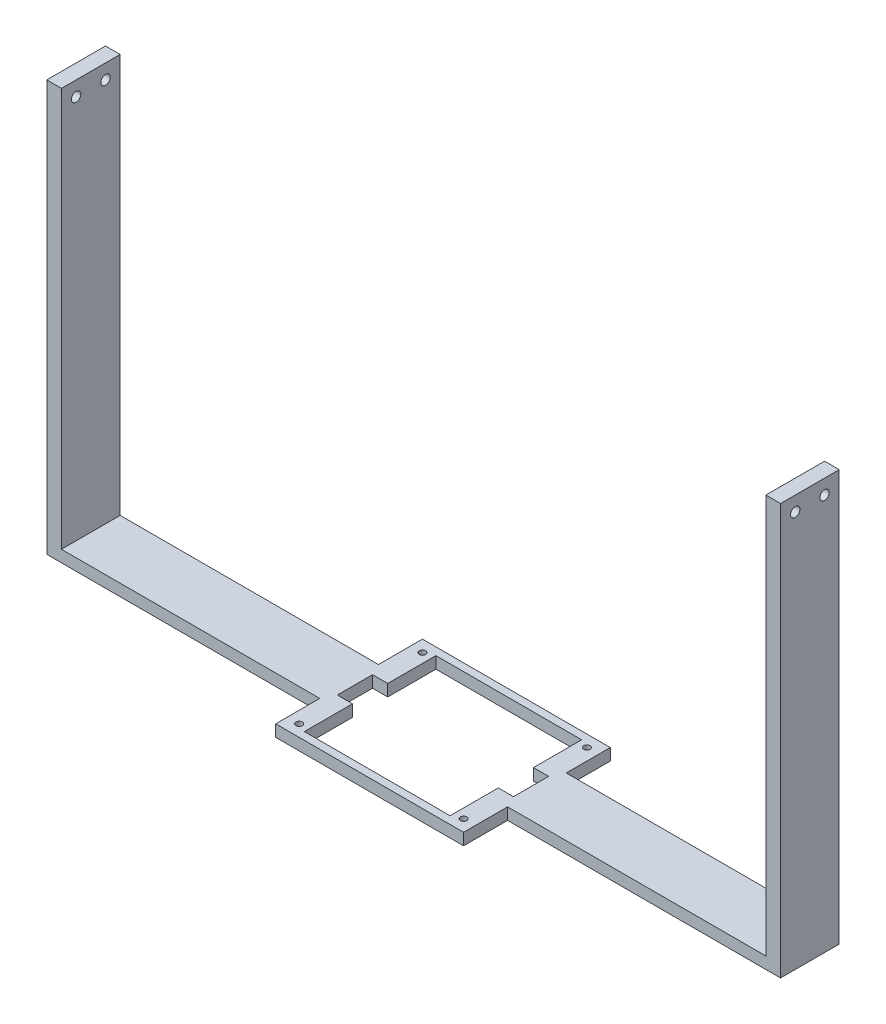
SolidWorks part; units mm, degrees
ref_plane "前视基准面" through (0, 0, 0) normal (0, 0, 1) x (1, 0, 0)
ref_plane "上视基准面" through (0, 0, 0) normal (0, 1, 0) x (1, 0, 0)
ref_plane "右视基准面" through (0, 0, 0) normal (1, 0, 0) x (0, 0, -1)
sketch "草图1" plane through (0, 0, 0) normal (0, 1, 0) x (1, 0, 0)
  line L0 (0, 385.0198) -> (0, -385.0198) construction
  line L1 (-385.0198, 0) -> (385.0198, 0) construction
  line L3 (125, 10) -> (-125, 10)
  line L4 (125, 10) -> (125, -10)
  line L5 (125, -10) -> (-125, -10)
  line L6 (-125, 10) -> (-125, -10)
  line L7 (125, 10) -> (-125, -10) construction
  line L8 (125, -10) -> (-125, 10) construction
  line L9 (-30, -6) -> (30, -6)
  line L10 (-30, -6) -> (-30, 6)
  line L11 (-30, 6) -> (30, 6)
  line L12 (30, -6) -> (30, 6)
  line L13 (-30, -6) -> (30, 6) construction
  line L14 (-30, 6) -> (30, -6) construction
  point P5 (0, 0)
  point P11 (0, 0)
  dimension "D1" = 250
  dimension "D2" = 20
  dimension "D3" = 4
  dimension "D4" = 60
extrude "凸台-拉伸1" add sketch "草图1" along normal blind 4
sketch "草图2" plane through (-125, 0, 0) normal (-1, 0, 0) x (0, 0, 1)
  line L0 (-10, 0) -> (-10, 140)
  line L1 (-10, 0) -> (10, 0)
  line L2 (10, 0) -> (10, 140)
  line L3 (10, 140) -> (-10, 140)
  line L4 (-10, 135) -> (10, 135) construction
  line L5 (0, 0) -> (0, 21.7153) construction
  circle A0 centre (-5, 135) radius 1.6
  circle A1 centre (5, 135) radius 1.6
  dimension "D2" = 5
  dimension "D3" = 3.2
  dimension "D1" = 140
  dimension "D4" = 5
extrude "凸台-拉伸2" add sketch "草图2" against normal blind 5
mirror "镜向1" about plane through (0, 0, 0) normal (1, 0, 0) of "凸台-拉伸2"
sketch "草图3" plane through (0, 4, 0) normal (0, 1, 0) x (1, 0, 0)
  line L0 (0, 10) -> (0, 25) construction
  line L1 (-28, 21) -> (28, 21) construction
  line L2 (-28, 21) -> (-28, -21) construction
  line L3 (-28, -21) -> (28, -21) construction
  line L4 (28, 21) -> (28, -21) construction
  line L5 (-28, 21) -> (28, -21) construction
  line L6 (-28, -21) -> (28, 21) construction
  line L7 (120, 10) -> (-120, 10) construction
  line L8 (32, 25) -> (-32, 25)
  line L9 (-32, 25) -> (-32, 10)
  line L10 (0, 0) -> (-59.6474, 0) construction
  line L11 (32, 25) -> (32, 10)
  line L12 (32, -25) -> (32, -10)
  line L13 (32, -25) -> (-32, -25)
  line L14 (-32, -25) -> (-32, -10)
  line L15 (-32, -10) -> (32, -10)
  line L16 (-32, 10) -> (32, 10)
  circle A0 centre (-28, 21) radius 1.1
  circle A1 centre (-28, -21) radius 1.1
  circle A2 centre (28, -21) radius 1.1
  circle A3 centre (28, 21) radius 1.1
  point P0 (0, 0)
  dimension "D3" = 2.2
  dimension "D1" = 56
  dimension "D2" = 42
  dimension "D4" = 4
  dimension "D5" = 4
extrude "凸台-拉伸3" add sketch "草图3" against normal blind 4
sketch "草图4" plane through (0, 4, 0) normal (0, 1, 0) x (1, 0, 0)
  line L1 (-24.8267, 22.4077) -> (24.8267, 22.4077)
  line L2 (-24.8267, 22.4077) -> (-24.8267, -22.4077)
  line L3 (-24.8267, -22.4077) -> (24.8267, -22.4077)
  line L4 (24.8267, 22.4077) -> (24.8267, -22.4077)
  line L5 (-24.8267, 22.4077) -> (24.8267, -22.4077) construction
  line L6 (-24.8267, -22.4077) -> (24.8267, 22.4077) construction
  point P0 (0, 0)
  point P5 (-24.8267, 22.4077)
extrude "切除-拉伸1" cut sketch "草图4" against normal blind 4
